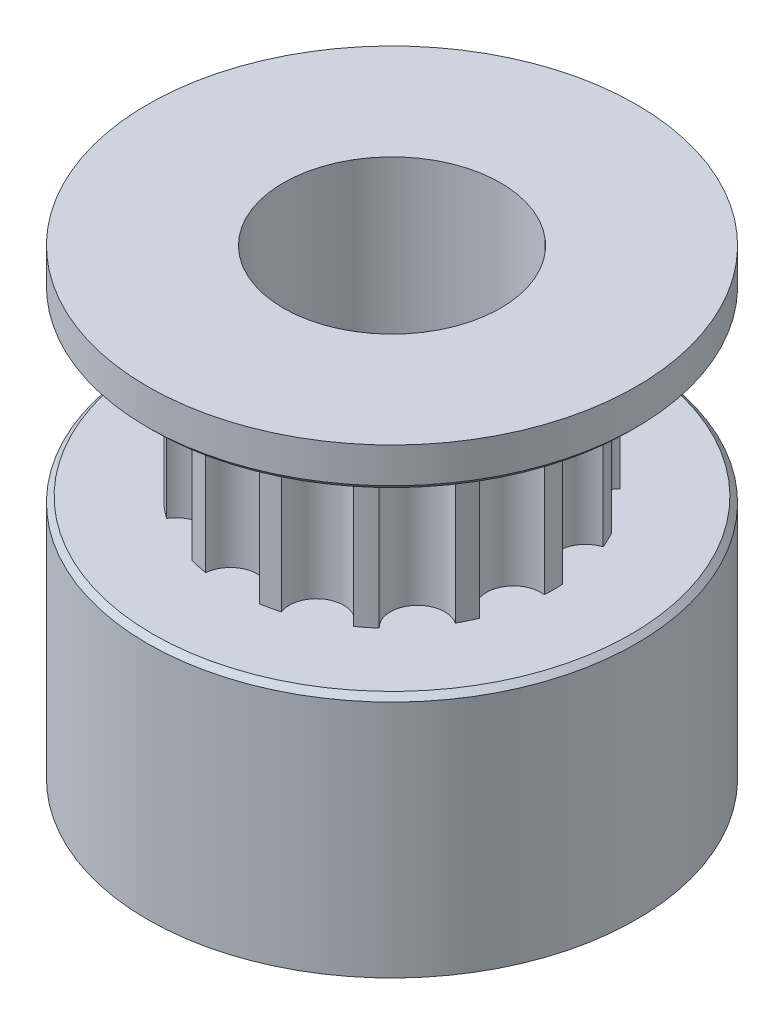
SolidWorks part; units mm, degrees
ref_plane "前视基准面" through (0, 0, 0) normal (0, 0, 1) x (1, 0, 0)
ref_plane "上视基准面" through (0, 0, 0) normal (0, 1, 0) x (1, 0, 0)
ref_plane "右视基准面" through (0, 0, 0) normal (1, 0, 0) x (0, 0, -1)
sketch "草图2" plane through (0, 0, 0) normal (0, 1, 0) x (1, 0, 0)
  circle A0 centre (0, 0) radius 9
  dimension "D1" = 18
extrude "凸台-拉伸1" add sketch "草图2" along normal blind 9
sketch "草图3" plane through (0, 9, 0) normal (0, 1, 0) x (1, 0, 0)
  arc A0 (-3.4442, 4.8553) -> (-3.9672, 4.4382) centre (0, 0) ccw
  arc A1 (-0.9965, 5.8689) -> (0.9965, 5.8689) centre (0, 5.9528) ccw
  arc A2 (1.6486, 5.72) -> (3.4442, 4.8553) centre (2.5828, 5.3633) ccw
  arc A3 (3.9672, 4.4382) -> (5.2097, 2.8801) centre (4.6541, 3.7115) ccw
  arc A4 (5.5, 2.2774) -> (5.9434, 0.3345) centre (5.8036, 1.3246) ccw
  arc A5 (5.9434, -0.3345) -> (5.5, -2.2774) centre (5.8036, -1.3246) ccw
  arc A6 (5.2097, -2.8801) -> (3.9672, -4.4382) centre (4.6541, -3.7115) ccw
  arc A7 (3.4442, -4.8553) -> (1.6486, -5.72) centre (2.5828, -5.3633) ccw
  arc A8 (0.9965, -5.8689) -> (-0.9965, -5.8689) centre (0, -5.9528) ccw
  arc A9 (-1.6486, -5.72) -> (-3.4442, -4.8553) centre (-2.5828, -5.3633) ccw
  arc A10 (-3.9672, -4.4382) -> (-5.2097, -2.8801) centre (-4.6541, -3.7115) ccw
  arc A11 (-5.5, -2.2774) -> (-5.9434, -0.3345) centre (-5.8036, -1.3246) ccw
  arc A12 (-5.9434, 0.3345) -> (-5.5, 2.2774) centre (-5.8036, 1.3246) ccw
  arc A13 (-5.2097, 2.8801) -> (-3.9672, 4.4382) centre (-4.6541, 3.7115) ccw
  arc A14 (-3.4442, 4.8553) -> (-1.6486, 5.72) centre (-2.5828, 5.3633) ccw
  arc A15 (-0.9965, 5.8689) -> (-1.6486, 5.72) centre (0, 0) ccw
  arc A16 (1.6486, 5.72) -> (0.9965, 5.8689) centre (0, 0) ccw
  arc A17 (3.9672, 4.4382) -> (3.4442, 4.8553) centre (0, 0) ccw
  arc A18 (5.5, 2.2774) -> (5.2097, 2.8801) centre (0, 0) ccw
  arc A19 (5.9434, -0.3345) -> (5.9434, 0.3345) centre (0, 0) ccw
  arc A20 (5.2097, -2.8801) -> (5.5, -2.2774) centre (0, 0) ccw
  arc A21 (3.4442, -4.8553) -> (3.9672, -4.4382) centre (0, 0) ccw
  arc A22 (0.9965, -5.8689) -> (1.6486, -5.72) centre (0, 0) ccw
  arc A23 (-1.6486, -5.72) -> (-0.9965, -5.8689) centre (0, 0) ccw
  arc A24 (-3.9672, -4.4382) -> (-3.4442, -4.8553) centre (0, 0) ccw
  arc A25 (-5.5, -2.2774) -> (-5.2097, -2.8801) centre (0, 0) ccw
  arc A26 (-5.9434, 0.3345) -> (-5.9434, -0.3345) centre (0, 0) ccw
  arc A27 (-5.2097, 2.8801) -> (-5.5, 2.2774) centre (0, 0) ccw
  point P34 (0, 0)
  dimension "D1" = 2
  dimension "D2" = 14
extrude "凸台-拉伸2" add sketch "草图3" along normal blind 6.5
sketch "草图4" plane through (0, 15.5, 0) normal (0, 1, 0) x (1, 0, 0)
  circle A0 centre (0, 0) radius 9
extrude "凸台-拉伸3" add sketch "草图4" along normal blind 1.5
sketch "草图5" plane through (0, 17, 0) normal (0, 1, 0) x (1, 0, 0)
  circle A0 centre (0, 0) radius 4
  dimension "D1" = 8
extrude "切除-拉伸1" cut sketch "草图5" against normal through all
chamfer "倒角1" distance 0.2 angle 45 2 edges at (0, 15.5, 9) (0, 9, 9)
